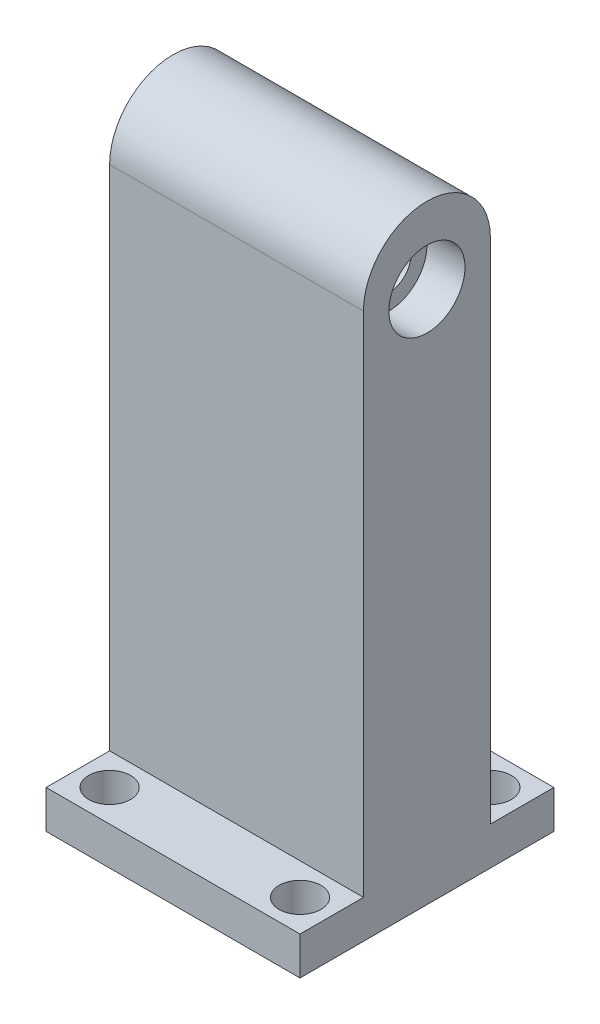
SolidWorks part; units mm, degrees
ref_plane "Front Plane" through (0, 0, 0) normal (0, 0, 1) x (1, 0, 0)
ref_plane "Top Plane" through (0, 0, 0) normal (0, 1, 0) x (1, 0, 0)
ref_plane "Right Plane" through (0, 0, 0) normal (1, 0, 0) x (0, 0, -1)
sketch "Sketch1" plane through (0, 0, 0) normal (0, 1, 0) x (1, 0, 0)
  line L1 (-10, 10) -> (10, 10)
  line L2 (-10, 10) -> (-10, -10)
  line L3 (-10, -10) -> (10, -10)
  line L4 (10, 10) -> (10, -10)
  line L5 (-10, 10) -> (10, -10) construction
  line L6 (-10, -10) -> (10, 10) construction
  point P0 (0, 0)
  dimension "D1" = 20
  dimension "D2" = 20
extrude "Boss-Extrude1" add sketch "Sketch1" along normal blind 52
sketch "Sketch2" plane through (10, 0, 0) normal (1, 0, 0) x (0, 0, -1)
  line L0 (0, 55) -> (0, -55) construction
  line L1 (-10, 52) -> (10, 52) construction
  circle A0 centre (0, 42) radius 3
  dimension "D1" = 6
  dimension "D2" = 10
extrude "Cut-Extrude1" cut sketch "Sketch2" against normal blind 3
sketch "Sketch3" plane through (7, 0, 0) normal (1, 0, 0) x (0, 0, -1)
  circle A0 centre (0, 42) radius 1.75
  dimension "D1" = 3.5
extrude "Cut-Extrude2" cut sketch "Sketch3" against normal through all
sketch "Sketch4" plane through (-10, 0, 0) normal (-1, 0, 0) x (0, 0, 1)
  circle A0 centre (0, 42) radius 3
  dimension "D1" = 6
extrude "Cut-Extrude3" cut sketch "Sketch4" against normal blind 3
sketch "Sketch5" plane through (0, 52, 0) normal (0, 1, 0) x (1, 0, 0)
  line L0 (-10, 10) -> (-10, -10) construction
  line L1 (10, 10) -> (-10, 10) construction
  line L2 (-10, -10) -> (10, -10) construction
  line L3 (10, -10) -> (10, 10) construction
  circle A0 centre (-7.5, 7.5) radius 1.6496
  circle A1 centre (7.5, 7.5) radius 1.6496
  circle A2 centre (7.5, -7.5) radius 1.6496
  circle A3 centre (-7.5, -7.5) radius 1.6496
  point P8 (0, 0)
  point P9 (0, 0)
  point P10 (0, 0)
  point P11 (0, 0)
  dimension "D1" = 2.5
  dimension "D2" = 2.5
  dimension "D3" = 2.5
  dimension "D4" = 2.5
extrude "Cut-Extrude4" cut sketch "Sketch5" against normal through all
sketch "Sketch6" plane through (-10, 0, 0) normal (-1, 0, 0) x (0, 0, 1)
  line L0 (0, 0) -> (0, 3) construction
  line L1 (0, -11) -> (0, 11) construction
  line L2 (-10, 3) -> (-5, 3)
  line L3 (-10, 52) -> (-10, 0) construction
  line L4 (-5, 3) -> (-5, 43)
  line L5 (5, 43) -> (5, 3)
  line L6 (5, 3) -> (10, 3)
  line L7 (10, 52) -> (10, 0) construction
  line L8 (-10, 3) -> (-10, 52)
  line L9 (-10, 52) -> (10, 52)
  line L10 (10, 52) -> (10, 3)
  arc A0 (-5, 43) -> (5, 43) centre (0, 43) cw
  point P17 (0, 48)
  dimension "D4" = 48
  dimension "D1" = 3
  dimension "D2" = 5
  dimension "D3" = 5
extrude "Cut-Extrude5" cut sketch "Sketch6" against normal through all
